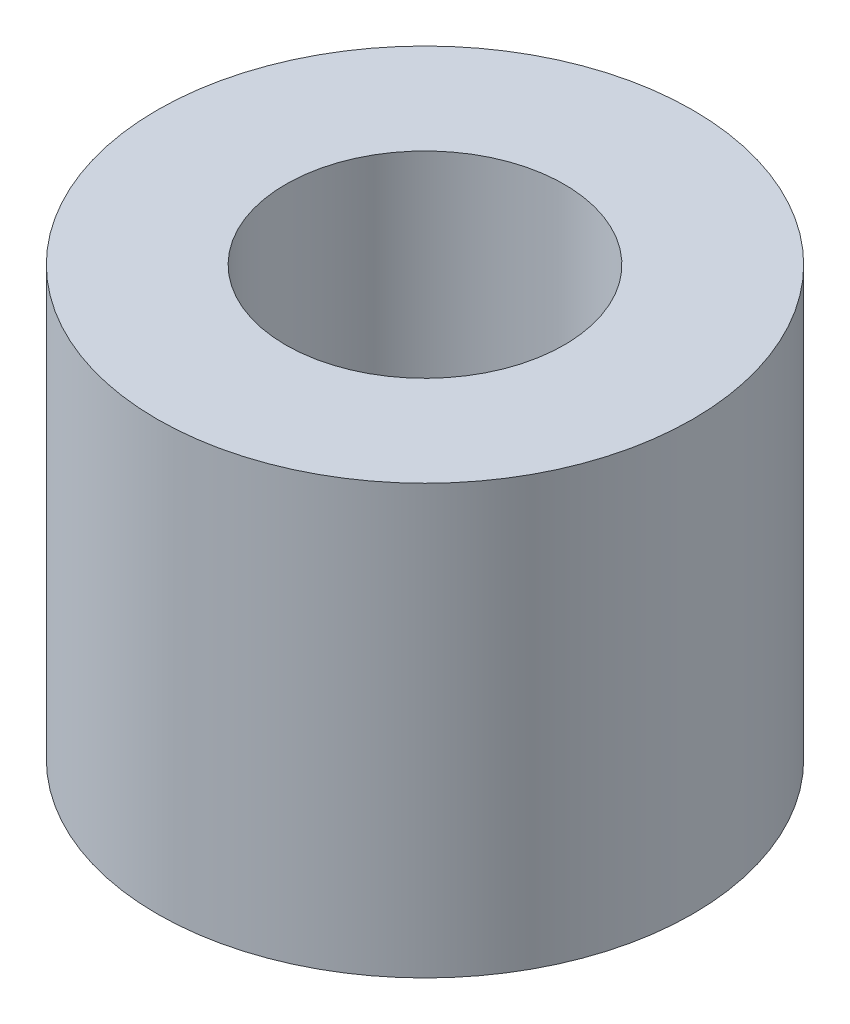
SolidWorks part; units mm, degrees
ref_plane "Front Plane" through (0, 0, 0) normal (0, 0, 1) x (1, 0, 0)
ref_plane "Top Plane" through (0, 0, 0) normal (0, 1, 0) x (1, 0, 0)
ref_plane "Right Plane" through (0, 0, 0) normal (1, 0, 0) x (0, 0, -1)
sketch "Sketch1" plane through (0, 0, 0) normal (0, 1, 0) x (1, 0, 0)
  circle A0 centre (0, 0) radius 2.6
  circle A1 centre (0, 0) radius 5
  dimension "D1" = 5.2
  dimension "D2" = 10
extrude "Boss-Extrude1" add sketch "Sketch1" along normal blind 8
sketch "Sketch2" plane through (0, 8, 0) normal (0, 1, 0) x (1, 0, 0)
  point P0 (0, 0)
sketch "Sketch3" plane through (0, 0, 0) normal (0, -1, 0) x (1, 0, 0)
  point P0 (0, 0)
